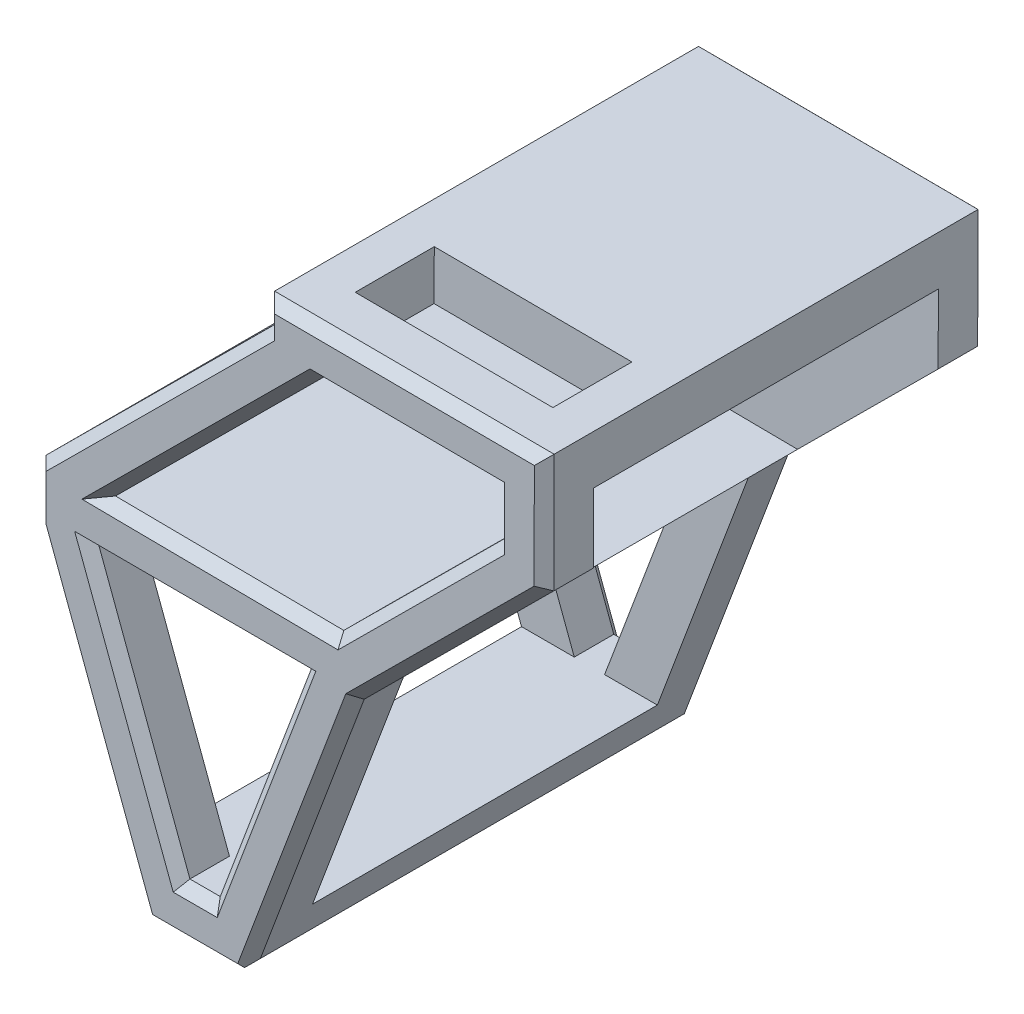
SolidWorks part; units mm, degrees
ref_plane "Front Plane" through (0, 0, 0) normal (0, 0, 1) x (1, 0, 0)
ref_plane "Top Plane" through (0, 0, 0) normal (0, 1, 0) x (1, 0, 0)
ref_plane "Right Plane" through (0, 0, 0) normal (1, 0, 0) x (0, 0, -1)
sketch "Model" plane through (0, 0, 0) normal (0, 0, 1) x (1, 0, 0)
  line L0 (66.3617, 66.2613) -> (38.0728, 66.412)
  line L1 (61.3484, 61.288) -> (43.0594, 61.3854)
  line L2 (38.0594, 61.412) -> (38.0461, 61.4121)
  line L3 (66.3617, 66.2613) -> (66.343, 59.2613)
  line L4 (38.0728, 66.412) -> (38.0649, 63.4645)
  line L5 (61.3484, 61.288) -> (61.3352, 56.3457)
  line L6 (66.343, 59.2613) -> (66.3297, 54.2614)
  line L7 (47.1342, 35.1678) -> (66.3297, 54.2614)
  line L8 (45.0764, 40.1733) -> (61.3352, 56.3457)
  line L9 (45.0764, 40.1733) -> (21.9685, 40.4013)
  line L10 (41.7989, 35.182) -> (20.2783, 35.2394)
  line L11 (21.9685, 40.4013) -> (43.0647, 61.3854)
  line L12 (14.9481, 40.4705) -> (38.0702, 63.4697)
  line L13 (14.9481, 40.4705) -> (14.9342, 35.2536)
  line L14 (26.0342, 5.5968) -> (36.0342, 5.5968)
  line L15 (14.9342, 35.2536) -> (26.0342, 5.5968)
  line L16 (20.2783, 35.2394) -> (29.5015, 10.5968)
  line L17 (36.0342, 5.5968) -> (47.1342, 35.1678)
  line L18 (32.5704, 10.5968) -> (41.7989, 35.182)
  line L19 (29.5015, 10.5968) -> (32.5704, 10.5968)
extrude "Boss-Extrude1" add sketch "Model" along normal blind 5
sketch "Sketch3" plane through (0, 0, 5) normal (0, 0, 1) x (1, 0, 0)
  line L5 (66.3617, 66.2613) -> (38.0728, 66.412) construction
  line L6 (66.3617, 66.2613) -> (38.0728, 66.412)
  line L7 (61.3484, 61.288) -> (43.0647, 61.3854) construction
  line L8 (61.3484, 61.288) -> (43.0647, 61.3854)
  line L9 (38.0649, 63.4645) -> (38.0649, 61.3854)
  line L10 (38.0649, 61.3854) -> (43.0647, 61.3854)
  line L11 (61.3484, 61.288) -> (66.3484, 61.288)
  line L12 (66.3617, 66.2613) -> (66.3297, 54.2614) construction
  line L13 (66.3484, 61.288) -> (66.3617, 66.2613)
  line L14 (38.0649, 63.4645) -> (38.0728, 66.412)
extrude "Boss-Extrude3" add sketch "Sketch3" along normal blind 5
sketch "Sketch4" plane through (0, 0, 10) normal (0, 0, 1) x (1, 0, 0)
  line L7 (66.3484, 61.288) -> (66.3617, 66.2613)
  line L8 (66.3617, 66.2613) -> (38.0728, 66.412)
  line L9 (38.0728, 66.412) -> (38.0649, 63.4645)
  line L10 (38.0649, 63.4645) -> (38.0649, 61.3854)
  line L11 (38.0649, 61.3854) -> (43.0647, 61.3854)
  line L12 (43.0647, 61.3854) -> (61.3484, 61.288)
  line L13 (61.3484, 61.288) -> (66.3484, 61.288)
  line L14 (66.3484, 61.288) -> (66.3617, 66.2613)
  line L15 (66.3617, 66.2613) -> (38.0728, 66.412)
  line L16 (38.0728, 66.412) -> (38.0649, 63.4645)
  line L17 (38.0649, 63.4645) -> (38.0649, 61.3854)
  line L18 (38.0649, 61.3854) -> (43.0647, 61.3854)
  line L19 (43.0647, 61.3854) -> (61.3484, 61.288)
  line L20 (61.3484, 61.288) -> (66.3484, 61.288)
  dimension "D1" = 0
extrude "Boss-Extrude4" add sketch "Sketch4" along normal blind 26.9
sketch "Sketch5" plane through (0.3283, 61.6131, 0) normal (-0.0053, -1, 0) x (1, -0.0053, 0)
  line L0 (51.879, 36.9) -> (51.879, 31.9) construction
  line L1 (42.737, 36.9) -> (61.021, 36.9) construction
  line L2 (37.7373, 36.9) -> (42.737, 36.9) construction
  line L3 (61.879, 31.9) -> (41.879, 31.9)
  line L4 (61.879, 31.9) -> (61.879, 36.9)
  line L5 (61.879, 36.9) -> (41.879, 36.9)
  line L6 (41.879, 31.9) -> (41.879, 36.9)
  line L7 (61.879, 31.9) -> (41.879, 36.9) construction
  line L8 (61.879, 36.9) -> (41.879, 31.9) construction
  point P4 (51.879, 34.4)
extrude "Cut-Extrude2" cut sketch "Sketch5" against normal blind 5.9
sketch "Sketch7" plane through (0.3283, 61.6131, 0) normal (0.0053, 1, 0) x (1, -0.0053, 0)
  line L4 (42.737, -31.9) -> (41.879, -31.9)
  line L5 (41.879, -31.9) -> (41.879, -36.9)
  line L6 (41.879, -36.9) -> (42.737, -36.9)
  line L7 (42.737, -36.9) -> (42.737, -31.9)
  line L8 (42.737, -31.9) -> (41.879, -31.9)
  line L9 (41.879, -31.9) -> (41.879, -36.9)
  line L10 (41.879, -36.9) -> (42.737, -36.9)
  line L11 (42.737, -36.9) -> (42.737, -31.9)
  dimension "D1" = 0
extrude "Cut-Extrude3" cut sketch "Sketch7" against normal mid plane 5.9
sketch "Sketch8" plane through (0, 0, 36.9) normal (0, 0, 1) x (1, 0, 0)
  line L4 (66.3617, 66.2613) -> (62.233, 66.2833)
  line L5 (38.0649, 61.3854) -> (42.2067, 61.3854)
  line L6 (42.2067, 61.3854) -> (42.2333, 66.3899)
  line L7 (42.2333, 66.3899) -> (38.0728, 66.412)
  line L8 (38.0728, 66.412) -> (38.0649, 63.4645)
  line L9 (38.0649, 63.4645) -> (38.0649, 61.3854)
  line L10 (38.0649, 61.3854) -> (42.2067, 61.3854)
  line L11 (42.2067, 61.3854) -> (42.2333, 66.3899)
  line L12 (42.2333, 66.3899) -> (38.0728, 66.412)
  line L13 (38.0728, 66.412) -> (38.0649, 63.4645)
  line L14 (38.0649, 63.4645) -> (38.0649, 61.3854)
  line L15 (62.233, 66.2833) -> (62.2064, 61.288)
  line L16 (62.2064, 61.288) -> (66.3484, 61.288)
  line L17 (66.3484, 61.288) -> (66.3617, 66.2613)
  line L18 (66.3617, 66.2613) -> (62.233, 66.2833)
  line L19 (62.233, 66.2833) -> (62.2064, 61.288)
  line L20 (62.2064, 61.288) -> (66.3484, 61.288)
  line L21 (66.3484, 61.288) -> (66.3617, 66.2613)
  dimension "D1" = 0
  dimension "D2" = 0
extrude "Boss-Extrude5" add sketch "Sketch8" along normal blind 3
sketch "Sketch9" plane through (0, 0, 39.9) normal (0, 0, 1) x (1, 0, 0)
  line L4 (66.3484, 61.288) -> (66.3617, 66.2613)
  line L5 (38.0649, 63.4645) -> (38.0649, 61.3854)
  line L6 (42.2067, 61.3854) -> (43.0647, 61.3854)
  line L7 (43.0647, 61.3854) -> (61.3484, 61.288)
  line L8 (61.3484, 61.288) -> (62.2064, 61.288)
  line L9 (62.2064, 61.288) -> (62.233, 66.2833)
  line L10 (62.233, 66.2833) -> (42.2333, 66.3899)
  line L11 (42.2333, 66.3899) -> (42.2067, 61.3854)
  line L12 (42.2067, 61.3854) -> (43.0647, 61.3854)
  line L13 (43.0647, 61.3854) -> (61.3484, 61.288)
  line L14 (61.3484, 61.288) -> (62.2064, 61.288)
  line L15 (62.2064, 61.288) -> (62.233, 66.2833)
  line L16 (62.233, 66.2833) -> (42.2333, 66.3899)
  line L17 (42.2333, 66.3899) -> (42.2067, 61.3854)
  line L18 (38.0649, 61.3854) -> (42.2067, 61.3854)
  line L19 (42.2067, 61.3854) -> (42.2333, 66.3899)
  line L20 (42.2333, 66.3899) -> (38.0728, 66.412)
  line L21 (38.0728, 66.412) -> (38.0649, 63.4645)
  line L22 (38.0649, 63.4645) -> (38.0649, 61.3854)
  line L23 (38.0649, 61.3854) -> (42.2067, 61.3854)
  line L24 (42.2067, 61.3854) -> (42.2333, 66.3899)
  line L25 (42.2333, 66.3899) -> (38.0728, 66.412)
  line L26 (38.0728, 66.412) -> (38.0649, 63.4645)
  line L27 (66.3617, 66.2613) -> (62.233, 66.2833)
  line L28 (62.233, 66.2833) -> (62.2064, 61.288)
  line L29 (62.2064, 61.288) -> (66.3484, 61.288)
  line L30 (66.3484, 61.288) -> (66.3617, 66.2613)
  line L31 (66.3617, 66.2613) -> (62.233, 66.2833)
  line L32 (62.233, 66.2833) -> (62.2064, 61.288)
  line L33 (62.2064, 61.288) -> (66.3484, 61.288)
  line M16 (66.3484, 61.288) -> (66.3617, 66.2613)
  line M17 (66.3617, 66.2613) -> (62.233, 66.2833)
  line M18 (62.233, 66.2833) -> (62.2064, 61.288)
  line M19 (62.2064, 61.288) -> (66.3484, 61.288)
  dimension "D1" = 0
  dimension "D2" = 0
  dimension "D3" = 0
extrude "Boss-Extrude6" add sketch "Sketch9" along normal blind 5 contours L16 L17 L12 L13 L14 M18 | L25 L26 L22 L23 L17 | M19 M16 M17 M18
sketch "Sketch10" plane through (0, 0, 44.9) normal (0, 0, 1) x (1, 0, 0)
  line L0 (29.5015, 10.5968) -> (32.5704, 10.5968) construction
  line L1 (20.2783, 35.2394) -> (29.5015, 10.5968) construction
  line L2 (41.7989, 35.182) -> (20.2783, 35.2394) construction
  line L3 (32.5704, 10.5968) -> (41.7989, 35.182) construction
  line L4 (29.5015, 10.5968) -> (32.5704, 10.5968)
  line L5 (20.2783, 35.2394) -> (29.5015, 10.5968)
  line L6 (41.7989, 35.182) -> (20.2783, 35.2394)
  line L7 (32.5704, 10.5968) -> (41.7989, 35.182)
  line L14 (66.3484, 61.288) -> (61.3484, 61.288)
  line L15 (61.3484, 61.288) -> (61.3352, 56.3457)
  line L16 (61.3352, 56.3457) -> (45.0764, 40.1733)
  line L17 (45.0764, 40.1733) -> (21.9685, 40.4013)
  line L18 (21.9685, 40.4013) -> (43.0647, 61.3854)
  line L19 (43.0647, 61.3854) -> (38.0649, 61.3854)
  line L20 (38.0649, 61.3854) -> (38.0649, 63.4645)
  line L21 (38.0649, 63.4645) -> (14.9481, 40.4705)
  line L22 (14.9481, 40.4705) -> (14.9342, 35.2536)
  line L23 (14.9342, 35.2536) -> (26.0342, 5.5968)
  line L24 (26.0342, 5.5968) -> (36.0342, 5.5968)
  line L25 (36.0342, 5.5968) -> (47.1342, 35.1678)
  line L26 (47.1342, 35.1678) -> (66.3297, 54.2614)
  line L27 (66.3297, 54.2614) -> (66.3484, 61.288)
  line L28 (66.3484, 61.288) -> (61.3484, 61.288)
  line L29 (61.3484, 61.288) -> (61.3352, 56.3457)
  line L30 (61.3352, 56.3457) -> (45.0764, 40.1733)
  line L31 (45.0764, 40.1733) -> (21.9685, 40.4013)
  line L32 (21.9685, 40.4013) -> (43.0647, 61.3854)
  line L33 (43.0647, 61.3854) -> (38.0649, 61.3854)
  line L34 (38.0649, 61.3854) -> (38.0649, 63.4645)
  line L35 (38.0649, 63.4645) -> (14.9481, 40.4705)
  line L36 (14.9481, 40.4705) -> (14.9342, 35.2536)
  line L37 (14.9342, 35.2536) -> (26.0342, 5.5968)
  line L38 (26.0342, 5.5968) -> (36.0342, 5.5968)
  line L39 (36.0342, 5.5968) -> (47.1342, 35.1678)
  line L40 (47.1342, 35.1678) -> (66.3297, 54.2614)
  line L41 (66.3297, 54.2614) -> (66.3484, 61.288)
  dimension "D1" = 0
extrude "Boss-Extrude7" add sketch "Sketch10" against normal blind 5
sketch "Sketch11" plane through (0, 0, 5) normal (0, 0, 1) x (1, 0, 0)
  line L0 (14.9342, 35.2536) -> (26.0342, 5.5968) construction
  line L1 (24.1628, 10.5968) -> (26.0342, 5.5968)
  line L2 (36.0342, 5.5968) -> (47.1342, 35.1678) construction
  line L3 (36.0342, 5.5968) -> (37.911, 10.5968)
  line L4 (26.0342, 5.5968) -> (36.0342, 5.5968) construction
  line L5 (26.0342, 5.5968) -> (36.0342, 5.5968)
  line L6 (24.1628, 10.5968) -> (37.911, 10.5968)
extrude "Boss-Extrude8" add sketch "Sketch11" along normal blind 35
sketch "Sketch12" plane through (0, 0, 5) normal (0, 0, 1) x (1, 0, 0)
  line L0 (45.0764, 40.1733) -> (21.9685, 40.4013) construction
  line L1 (52.0968, 40.1041) -> (14.9481, 40.4705)
  line L2 (41.7989, 35.182) -> (20.2783, 35.2394) construction
  line L3 (47.1342, 35.1678) -> (14.9342, 35.2536)
  line L4 (47.1342, 35.1678) -> (66.3297, 54.2614) construction
  line L5 (47.1342, 35.1678) -> (52.0968, 40.1041)
  line L6 (14.9481, 40.4705) -> (14.9342, 35.2536) construction
  line L7 (14.9481, 40.4705) -> (14.9342, 35.2536)
extrude "Boss-Extrude10" add sketch "Sketch12" along normal blind 35
chamfer "Chamfer2" distance 1 angle 45 36 edges at (41.5842, 20.3823, 0) (56.7319, 44.7146, 0) (66.3457, 60.2613, 0) (52.2172, 66.3367, 0) (38.0688, 64.9382, 0) (26.5065, 51.9675, 0) (14.9412, 37.8621, 0) (20.4842, 20.4252, 0) (31.0342, 5.5968, 0) (32.5166, 50.8933, 0) (52.2065, 61.3367, 0) (61.3418, 58.8168, 0) (53.2058, 48.2595, 0) (33.5225, 40.2873, 0) (24.8899, 22.9181, 0) (31.0386, 35.2107, 0) (37.1846, 22.8894, 0) (31.036, 10.5968, 0) (31.036, 10.5968, 44.9) (37.1846, 22.8894, 44.9) (31.0386, 35.2107, 44.9) (24.8899, 22.9181, 44.9) (66.3457, 60.2613, 44.9) (56.7319, 44.7146, 44.9) (41.5842, 20.3823, 44.9) (31.0342, 5.5968, 44.9) (20.4842, 20.4252, 44.9) (14.9412, 37.8621, 44.9) (26.5065, 51.9675, 44.9) (38.0688, 64.9382, 44.9) (52.2172, 66.3367, 44.9) (33.5225, 40.2873, 44.9) (53.2058, 48.2595, 44.9) (61.3418, 58.8168, 44.9) (52.2065, 61.3367, 44.9) (32.5166, 50.8933, 44.9)
chamfer "Chamfer3" distance 1 angle 45 2 edges at (26.0342, 5.5968, 22.45) (36.0342, 5.5968, 22.45)
